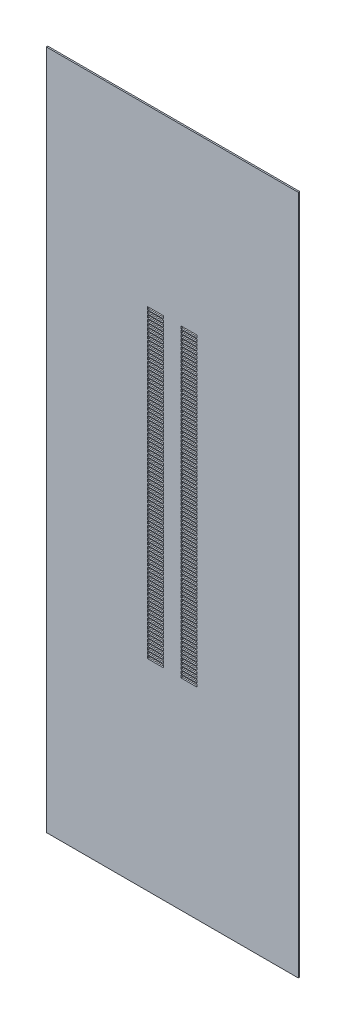
SolidWorks part; units mm, degrees
ref_plane "Front Plane" through (0, 0, 0) normal (0, 0, 1) x (1, 0, 0)
ref_plane "Top Plane" through (0, 0, 0) normal (0, 1, 0) x (1, 0, 0)
ref_plane "Right Plane" through (0, 0, 0) normal (1, 0, 0) x (0, 0, -1)
sketch "Sketch1" plane through (0, 0, 0) normal (0, 0, 1) x (1, 0, 0)
  line L1340 (-1.19, -0.37) -> (-1.19, 0)
  line L1341 (-1.19, 0) -> (-3.41, 0)
  line L1342 (-3.41, 0) -> (-3.41, -0.37)
  line L1343 (-3.41, -0.37) -> (-1.19, -0.37)
  line L2016 (-1.19, 0) -> (1.19, 0) construction
  line L2017 (0, 0) -> (0, 7.5425) construction
  line L2018 (1.19, -0.37) -> (1.19, 0)
  line L2019 (3.41, -0.37) -> (1.19, -0.37)
  line L2020 (3.41, 0) -> (3.41, -0.37)
  line L2021 (1.19, 0) -> (3.41, 0)
  line L2022 (1.19, -0.5) -> (3.41, -0.5)
  line L2023 (3.41, -0.5) -> (3.41, -0.87)
  line L2024 (3.41, -0.87) -> (1.19, -0.87)
  line L2025 (1.19, -0.87) -> (1.19, -0.5)
  line L2026 (-1.19, -0.5) -> (-3.41, -0.5)
  line L2027 (-3.41, -0.5) -> (-3.41, -0.87)
  line L2028 (-3.41, -0.87) -> (-1.19, -0.87)
  line L2029 (-1.19, -0.87) -> (-1.19, -0.5)
  line L2030 (1.19, -1) -> (3.41, -1)
  line L2031 (3.41, -1) -> (3.41, -1.37)
  line L2032 (3.41, -1.37) -> (1.19, -1.37)
  line L2033 (1.19, -1.37) -> (1.19, -1)
  line L2034 (-1.19, -1) -> (-3.41, -1)
  line L2035 (-3.41, -1) -> (-3.41, -1.37)
  line L2036 (-3.41, -1.37) -> (-1.19, -1.37)
  line L2037 (-1.19, -1.37) -> (-1.19, -1)
  line L2038 (1.19, -1.5) -> (3.41, -1.5)
  line L2039 (3.41, -1.5) -> (3.41, -1.87)
  line L2040 (3.41, -1.87) -> (1.19, -1.87)
  line L2041 (1.19, -1.87) -> (1.19, -1.5)
  line L2042 (-1.19, -1.5) -> (-3.41, -1.5)
  line L2043 (-3.41, -1.5) -> (-3.41, -1.87)
  line L2044 (-3.41, -1.87) -> (-1.19, -1.87)
  line L2045 (-1.19, -1.87) -> (-1.19, -1.5)
  line L2046 (1.19, -2) -> (3.41, -2)
  line L2047 (3.41, -2) -> (3.41, -2.37)
  line L2048 (3.41, -2.37) -> (1.19, -2.37)
  line L2049 (1.19, -2.37) -> (1.19, -2)
  line L2050 (-1.19, -2) -> (-3.41, -2)
  line L2051 (-3.41, -2) -> (-3.41, -2.37)
  line L2052 (-3.41, -2.37) -> (-1.19, -2.37)
  line L2053 (-1.19, -2.37) -> (-1.19, -2)
  line L2054 (1.19, -2.5) -> (3.41, -2.5)
  line L2055 (3.41, -2.5) -> (3.41, -2.87)
  line L2056 (3.41, -2.87) -> (1.19, -2.87)
  line L2057 (1.19, -2.87) -> (1.19, -2.5)
  line L2058 (-1.19, -2.5) -> (-3.41, -2.5)
  line L2059 (-3.41, -2.5) -> (-3.41, -2.87)
  line L2060 (-3.41, -2.87) -> (-1.19, -2.87)
  line L2061 (-1.19, -2.87) -> (-1.19, -2.5)
  line L2062 (1.19, -3) -> (3.41, -3)
  line L2063 (3.41, -3) -> (3.41, -3.37)
  line L2064 (3.41, -3.37) -> (1.19, -3.37)
  line L2065 (1.19, -3.37) -> (1.19, -3)
  line L2066 (-1.19, -3) -> (-3.41, -3)
  line L2067 (-3.41, -3) -> (-3.41, -3.37)
  line L2068 (-3.41, -3.37) -> (-1.19, -3.37)
  line L2069 (-1.19, -3.37) -> (-1.19, -3)
  line L2070 (1.19, -3.5) -> (3.41, -3.5)
  line L2071 (3.41, -3.5) -> (3.41, -3.87)
  line L2072 (3.41, -3.87) -> (1.19, -3.87)
  line L2073 (1.19, -3.87) -> (1.19, -3.5)
  line L2074 (-1.19, -3.5) -> (-3.41, -3.5)
  line L2075 (-3.41, -3.5) -> (-3.41, -3.87)
  line L2076 (-3.41, -3.87) -> (-1.19, -3.87)
  line L2077 (-1.19, -3.87) -> (-1.19, -3.5)
  line L2078 (1.19, -4) -> (3.41, -4)
  line L2079 (3.41, -4) -> (3.41, -4.37)
  line L2080 (3.41, -4.37) -> (1.19, -4.37)
  line L2081 (1.19, -4.37) -> (1.19, -4)
  line L2082 (-1.19, -4) -> (-3.41, -4)
  line L2083 (-3.41, -4) -> (-3.41, -4.37)
  line L2084 (-3.41, -4.37) -> (-1.19, -4.37)
  line L2085 (-1.19, -4.37) -> (-1.19, -4)
  line L2086 (1.19, -4.5) -> (3.41, -4.5)
  line L2087 (3.41, -4.5) -> (3.41, -4.87)
  line L2088 (3.41, -4.87) -> (1.19, -4.87)
  line L2089 (1.19, -4.87) -> (1.19, -4.5)
  line L2090 (-1.19, -4.5) -> (-3.41, -4.5)
  line L2091 (-3.41, -4.5) -> (-3.41, -4.87)
  line L2092 (-3.41, -4.87) -> (-1.19, -4.87)
  line L2093 (-1.19, -4.87) -> (-1.19, -4.5)
  line L2094 (1.19, -5) -> (3.41, -5)
  line L2095 (3.41, -5) -> (3.41, -5.37)
  line L2096 (3.41, -5.37) -> (1.19, -5.37)
  line L2097 (1.19, -5.37) -> (1.19, -5)
  line L2098 (-1.19, -5) -> (-3.41, -5)
  line L2099 (-3.41, -5) -> (-3.41, -5.37)
  line L2100 (-3.41, -5.37) -> (-1.19, -5.37)
  line L2101 (-1.19, -5.37) -> (-1.19, -5)
  line L2102 (1.19, -5.5) -> (3.41, -5.5)
  line L2103 (3.41, -5.5) -> (3.41, -5.87)
  line L2104 (3.41, -5.87) -> (1.19, -5.87)
  line L2105 (1.19, -5.87) -> (1.19, -5.5)
  line L2106 (-1.19, -5.5) -> (-3.41, -5.5)
  line L2107 (-3.41, -5.5) -> (-3.41, -5.87)
  line L2108 (-3.41, -5.87) -> (-1.19, -5.87)
  line L2109 (-1.19, -5.87) -> (-1.19, -5.5)
  line L2110 (1.19, -6) -> (3.41, -6)
  line L2111 (3.41, -6) -> (3.41, -6.37)
  line L2112 (3.41, -6.37) -> (1.19, -6.37)
  line L2113 (1.19, -6.37) -> (1.19, -6)
  line L2114 (-1.19, -6) -> (-3.41, -6)
  line L2115 (-3.41, -6) -> (-3.41, -6.37)
  line L2116 (-3.41, -6.37) -> (-1.19, -6.37)
  line L2117 (-1.19, -6.37) -> (-1.19, -6)
  line L2118 (1.19, -6.5) -> (3.41, -6.5)
  line L2119 (3.41, -6.5) -> (3.41, -6.87)
  line L2120 (3.41, -6.87) -> (1.19, -6.87)
  line L2121 (1.19, -6.87) -> (1.19, -6.5)
  line L2122 (-1.19, -6.5) -> (-3.41, -6.5)
  line L2123 (-3.41, -6.5) -> (-3.41, -6.87)
  line L2124 (-3.41, -6.87) -> (-1.19, -6.87)
  line L2125 (-1.19, -6.87) -> (-1.19, -6.5)
  line L2126 (1.19, -7) -> (3.41, -7)
  line L2127 (3.41, -7) -> (3.41, -7.37)
  line L2128 (3.41, -7.37) -> (1.19, -7.37)
  line L2129 (1.19, -7.37) -> (1.19, -7)
  line L2130 (-1.19, -7) -> (-3.41, -7)
  line L2131 (-3.41, -7) -> (-3.41, -7.37)
  line L2132 (-3.41, -7.37) -> (-1.19, -7.37)
  line L2133 (-1.19, -7.37) -> (-1.19, -7)
  line L2134 (1.19, -7.5) -> (3.41, -7.5)
  line L2135 (3.41, -7.5) -> (3.41, -7.87)
  line L2136 (3.41, -7.87) -> (1.19, -7.87)
  line L2137 (1.19, -7.87) -> (1.19, -7.5)
  line L2138 (-1.19, -7.5) -> (-3.41, -7.5)
  line L2139 (-3.41, -7.5) -> (-3.41, -7.87)
  line L2140 (-3.41, -7.87) -> (-1.19, -7.87)
  line L2141 (-1.19, -7.87) -> (-1.19, -7.5)
  line L2142 (1.19, -8) -> (3.41, -8)
  line L2143 (3.41, -8) -> (3.41, -8.37)
  line L2144 (3.41, -8.37) -> (1.19, -8.37)
  line L2145 (1.19, -8.37) -> (1.19, -8)
  line L2146 (-1.19, -8) -> (-3.41, -8)
  line L2147 (-3.41, -8) -> (-3.41, -8.37)
  line L2148 (-3.41, -8.37) -> (-1.19, -8.37)
  line L2149 (-1.19, -8.37) -> (-1.19, -8)
  line L2150 (1.19, -8.5) -> (3.41, -8.5)
  line L2151 (3.41, -8.5) -> (3.41, -8.87)
  line L2152 (3.41, -8.87) -> (1.19, -8.87)
  line L2153 (1.19, -8.87) -> (1.19, -8.5)
  line L2154 (-1.19, -8.5) -> (-3.41, -8.5)
  line L2155 (-3.41, -8.5) -> (-3.41, -8.87)
  line L2156 (-3.41, -8.87) -> (-1.19, -8.87)
  line L2157 (-1.19, -8.87) -> (-1.19, -8.5)
  line L2158 (1.19, -9) -> (3.41, -9)
  line L2159 (3.41, -9) -> (3.41, -9.37)
  line L2160 (3.41, -9.37) -> (1.19, -9.37)
  line L2161 (1.19, -9.37) -> (1.19, -9)
  line L2162 (-1.19, -9) -> (-3.41, -9)
  line L2163 (-3.41, -9) -> (-3.41, -9.37)
  line L2164 (-3.41, -9.37) -> (-1.19, -9.37)
  line L2165 (-1.19, -9.37) -> (-1.19, -9)
  line L2166 (1.19, -9.5) -> (3.41, -9.5)
  line L2167 (3.41, -9.5) -> (3.41, -9.87)
  line L2168 (3.41, -9.87) -> (1.19, -9.87)
  line L2169 (1.19, -9.87) -> (1.19, -9.5)
  line L2170 (-1.19, -9.5) -> (-3.41, -9.5)
  line L2171 (-3.41, -9.5) -> (-3.41, -9.87)
  line L2172 (-3.41, -9.87) -> (-1.19, -9.87)
  line L2173 (-1.19, -9.87) -> (-1.19, -9.5)
  line L2174 (1.19, -10) -> (3.41, -10)
  line L2175 (3.41, -10) -> (3.41, -10.37)
  line L2176 (3.41, -10.37) -> (1.19, -10.37)
  line L2177 (1.19, -10.37) -> (1.19, -10)
  line L2178 (-1.19, -10) -> (-3.41, -10)
  line L2179 (-3.41, -10) -> (-3.41, -10.37)
  line L2180 (-3.41, -10.37) -> (-1.19, -10.37)
  line L2181 (-1.19, -10.37) -> (-1.19, -10)
  line L2182 (1.19, -10.5) -> (3.41, -10.5)
  line L2183 (3.41, -10.5) -> (3.41, -10.87)
  line L2184 (3.41, -10.87) -> (1.19, -10.87)
  line L2185 (1.19, -10.87) -> (1.19, -10.5)
  line L2186 (-1.19, -10.5) -> (-3.41, -10.5)
  line L2187 (-3.41, -10.5) -> (-3.41, -10.87)
  line L2188 (-3.41, -10.87) -> (-1.19, -10.87)
  line L2189 (-1.19, -10.87) -> (-1.19, -10.5)
  line L2190 (1.19, -11) -> (3.41, -11)
  line L2191 (3.41, -11) -> (3.41, -11.37)
  line L2192 (3.41, -11.37) -> (1.19, -11.37)
  line L2193 (1.19, -11.37) -> (1.19, -11)
  line L2194 (-1.19, -11) -> (-3.41, -11)
  line L2195 (-3.41, -11) -> (-3.41, -11.37)
  line L2196 (-3.41, -11.37) -> (-1.19, -11.37)
  line L2197 (-1.19, -11.37) -> (-1.19, -11)
  line L2198 (1.19, -11.5) -> (3.41, -11.5)
  line L2199 (3.41, -11.5) -> (3.41, -11.87)
  line L2200 (3.41, -11.87) -> (1.19, -11.87)
  line L2201 (1.19, -11.87) -> (1.19, -11.5)
  line L2202 (-1.19, -11.5) -> (-3.41, -11.5)
  line L2203 (-3.41, -11.5) -> (-3.41, -11.87)
  line L2204 (-3.41, -11.87) -> (-1.19, -11.87)
  line L2205 (-1.19, -11.87) -> (-1.19, -11.5)
  line L2206 (1.19, -12) -> (3.41, -12)
  line L2207 (3.41, -12) -> (3.41, -12.37)
  line L2208 (3.41, -12.37) -> (1.19, -12.37)
  line L2209 (1.19, -12.37) -> (1.19, -12)
  line L2210 (-1.19, -12) -> (-3.41, -12)
  line L2211 (-3.41, -12) -> (-3.41, -12.37)
  line L2212 (-3.41, -12.37) -> (-1.19, -12.37)
  line L2213 (-1.19, -12.37) -> (-1.19, -12)
  line L2214 (1.19, -12.5) -> (3.41, -12.5)
  line L2215 (3.41, -12.5) -> (3.41, -12.87)
  line L2216 (3.41, -12.87) -> (1.19, -12.87)
  line L2217 (1.19, -12.87) -> (1.19, -12.5)
  line L2218 (-1.19, -12.5) -> (-3.41, -12.5)
  line L2219 (-3.41, -12.5) -> (-3.41, -12.87)
  line L2220 (-3.41, -12.87) -> (-1.19, -12.87)
  line L2221 (-1.19, -12.87) -> (-1.19, -12.5)
  line L2222 (1.19, -13) -> (3.41, -13)
  line L2223 (3.41, -13) -> (3.41, -13.37)
  line L2224 (3.41, -13.37) -> (1.19, -13.37)
  line L2225 (1.19, -13.37) -> (1.19, -13)
  line L2226 (-1.19, -13) -> (-3.41, -13)
  line L2227 (-3.41, -13) -> (-3.41, -13.37)
  line L2228 (-3.41, -13.37) -> (-1.19, -13.37)
  line L2229 (-1.19, -13.37) -> (-1.19, -13)
  line L2230 (1.19, -13.5) -> (3.41, -13.5)
  line L2231 (3.41, -13.5) -> (3.41, -13.87)
  line L2232 (3.41, -13.87) -> (1.19, -13.87)
  line L2233 (1.19, -13.87) -> (1.19, -13.5)
  line L2234 (-1.19, -13.5) -> (-3.41, -13.5)
  line L2235 (-3.41, -13.5) -> (-3.41, -13.87)
  line L2236 (-3.41, -13.87) -> (-1.19, -13.87)
  line L2237 (-1.19, -13.87) -> (-1.19, -13.5)
  line L2238 (1.19, -14) -> (3.41, -14)
  line L2239 (3.41, -14) -> (3.41, -14.37)
  line L2240 (3.41, -14.37) -> (1.19, -14.37)
  line L2241 (1.19, -14.37) -> (1.19, -14)
  line L2242 (-1.19, -14) -> (-3.41, -14)
  line L2243 (-3.41, -14) -> (-3.41, -14.37)
  line L2244 (-3.41, -14.37) -> (-1.19, -14.37)
  line L2245 (-1.19, -14.37) -> (-1.19, -14)
  line L2246 (1.19, -14.5) -> (3.41, -14.5)
  line L2247 (3.41, -14.5) -> (3.41, -14.87)
  line L2248 (3.41, -14.87) -> (1.19, -14.87)
  line L2249 (1.19, -14.87) -> (1.19, -14.5)
  line L2250 (-1.19, -14.5) -> (-3.41, -14.5)
  line L2251 (-3.41, -14.5) -> (-3.41, -14.87)
  line L2252 (-3.41, -14.87) -> (-1.19, -14.87)
  line L2253 (-1.19, -14.87) -> (-1.19, -14.5)
  line L2254 (1.19, -15) -> (3.41, -15)
  line L2255 (3.41, -15) -> (3.41, -15.37)
  line L2256 (3.41, -15.37) -> (1.19, -15.37)
  line L2257 (1.19, -15.37) -> (1.19, -15)
  line L2258 (-1.19, -15) -> (-3.41, -15)
  line L2259 (-3.41, -15) -> (-3.41, -15.37)
  line L2260 (-3.41, -15.37) -> (-1.19, -15.37)
  line L2261 (-1.19, -15.37) -> (-1.19, -15)
  line L2262 (1.19, -15.5) -> (3.41, -15.5)
  line L2263 (3.41, -15.5) -> (3.41, -15.87)
  line L2264 (3.41, -15.87) -> (1.19, -15.87)
  line L2265 (1.19, -15.87) -> (1.19, -15.5)
  line L2266 (-1.19, -15.5) -> (-3.41, -15.5)
  line L2267 (-3.41, -15.5) -> (-3.41, -15.87)
  line L2268 (-3.41, -15.87) -> (-1.19, -15.87)
  line L2269 (-1.19, -15.87) -> (-1.19, -15.5)
  line L2270 (1.19, -16) -> (3.41, -16)
  line L2271 (3.41, -16) -> (3.41, -16.37)
  line L2272 (3.41, -16.37) -> (1.19, -16.37)
  line L2273 (1.19, -16.37) -> (1.19, -16)
  line L2274 (-1.19, -16) -> (-3.41, -16)
  line L2275 (-3.41, -16) -> (-3.41, -16.37)
  line L2276 (-3.41, -16.37) -> (-1.19, -16.37)
  line L2277 (-1.19, -16.37) -> (-1.19, -16)
  line L2278 (1.19, -16.5) -> (3.41, -16.5)
  line L2279 (3.41, -16.5) -> (3.41, -16.87)
  line L2280 (3.41, -16.87) -> (1.19, -16.87)
  line L2281 (1.19, -16.87) -> (1.19, -16.5)
  line L2282 (-1.19, -16.5) -> (-3.41, -16.5)
  line L2283 (-3.41, -16.5) -> (-3.41, -16.87)
  line L2284 (-3.41, -16.87) -> (-1.19, -16.87)
  line L2285 (-1.19, -16.87) -> (-1.19, -16.5)
  line L2286 (1.19, -17) -> (3.41, -17)
  line L2287 (3.41, -17) -> (3.41, -17.37)
  line L2288 (3.41, -17.37) -> (1.19, -17.37)
  line L2289 (1.19, -17.37) -> (1.19, -17)
  line L2290 (-1.19, -17) -> (-3.41, -17)
  line L2291 (-3.41, -17) -> (-3.41, -17.37)
  line L2292 (-3.41, -17.37) -> (-1.19, -17.37)
  line L2293 (-1.19, -17.37) -> (-1.19, -17)
  line L2294 (1.19, -17.5) -> (3.41, -17.5)
  line L2295 (3.41, -17.5) -> (3.41, -17.87)
  line L2296 (3.41, -17.87) -> (1.19, -17.87)
  line L2297 (1.19, -17.87) -> (1.19, -17.5)
  line L2298 (-1.19, -17.5) -> (-3.41, -17.5)
  line L2299 (-3.41, -17.5) -> (-3.41, -17.87)
  line L2300 (-3.41, -17.87) -> (-1.19, -17.87)
  line L2301 (-1.19, -17.87) -> (-1.19, -17.5)
  line L2302 (1.19, -18) -> (3.41, -18)
  line L2303 (3.41, -18) -> (3.41, -18.37)
  line L2304 (3.41, -18.37) -> (1.19, -18.37)
  line L2305 (1.19, -18.37) -> (1.19, -18)
  line L2306 (-1.19, -18) -> (-3.41, -18)
  line L2307 (-3.41, -18) -> (-3.41, -18.37)
  line L2308 (-3.41, -18.37) -> (-1.19, -18.37)
  line L2309 (-1.19, -18.37) -> (-1.19, -18)
  line L2310 (1.19, -18.5) -> (3.41, -18.5)
  line L2311 (3.41, -18.5) -> (3.41, -18.87)
  line L2312 (3.41, -18.87) -> (1.19, -18.87)
  line L2313 (1.19, -18.87) -> (1.19, -18.5)
  line L2314 (-1.19, -18.5) -> (-3.41, -18.5)
  line L2315 (-3.41, -18.5) -> (-3.41, -18.87)
  line L2316 (-3.41, -18.87) -> (-1.19, -18.87)
  line L2317 (-1.19, -18.87) -> (-1.19, -18.5)
  line L2318 (1.19, -19) -> (3.41, -19)
  line L2319 (3.41, -19) -> (3.41, -19.37)
  line L2320 (3.41, -19.37) -> (1.19, -19.37)
  line L2321 (1.19, -19.37) -> (1.19, -19)
  line L2322 (-1.19, -19) -> (-3.41, -19)
  line L2323 (-3.41, -19) -> (-3.41, -19.37)
  line L2324 (-3.41, -19.37) -> (-1.19, -19.37)
  line L2325 (-1.19, -19.37) -> (-1.19, -19)
  line L2326 (1.19, -19.5) -> (3.41, -19.5)
  line L2327 (3.41, -19.5) -> (3.41, -19.87)
  line L2328 (3.41, -19.87) -> (1.19, -19.87)
  line L2329 (1.19, -19.87) -> (1.19, -19.5)
  line L2330 (-1.19, -19.5) -> (-3.41, -19.5)
  line L2331 (-3.41, -19.5) -> (-3.41, -19.87)
  line L2332 (-3.41, -19.87) -> (-1.19, -19.87)
  line L2333 (-1.19, -19.87) -> (-1.19, -19.5)
  line L2334 (1.19, -20) -> (3.41, -20)
  line L2335 (3.41, -20) -> (3.41, -20.37)
  line L2336 (3.41, -20.37) -> (1.19, -20.37)
  line L2337 (1.19, -20.37) -> (1.19, -20)
  line L2338 (-1.19, -20) -> (-3.41, -20)
  line L2339 (-3.41, -20) -> (-3.41, -20.37)
  line L2340 (-3.41, -20.37) -> (-1.19, -20.37)
  line L2341 (-1.19, -20.37) -> (-1.19, -20)
  line L2342 (1.19, -20.5) -> (3.41, -20.5)
  line L2343 (3.41, -20.5) -> (3.41, -20.87)
  line L2344 (3.41, -20.87) -> (1.19, -20.87)
  line L2345 (1.19, -20.87) -> (1.19, -20.5)
  line L2346 (-1.19, -20.5) -> (-3.41, -20.5)
  line L2347 (-3.41, -20.5) -> (-3.41, -20.87)
  line L2348 (-3.41, -20.87) -> (-1.19, -20.87)
  line L2349 (-1.19, -20.87) -> (-1.19, -20.5)
  line L2350 (1.19, -21) -> (3.41, -21)
  line L2351 (3.41, -21) -> (3.41, -21.37)
  line L2352 (3.41, -21.37) -> (1.19, -21.37)
  line L2353 (1.19, -21.37) -> (1.19, -21)
  line L2354 (-1.19, -21) -> (-3.41, -21)
  line L2355 (-3.41, -21) -> (-3.41, -21.37)
  line L2356 (-3.41, -21.37) -> (-1.19, -21.37)
  line L2357 (-1.19, -21.37) -> (-1.19, -21)
  line L2358 (1.19, -21.5) -> (3.41, -21.5)
  line L2359 (3.41, -21.5) -> (3.41, -21.87)
  line L2360 (3.41, -21.87) -> (1.19, -21.87)
  line L2361 (1.19, -21.87) -> (1.19, -21.5)
  line L2362 (-1.19, -21.5) -> (-3.41, -21.5)
  line L2363 (-3.41, -21.5) -> (-3.41, -21.87)
  line L2364 (-3.41, -21.87) -> (-1.19, -21.87)
  line L2365 (-1.19, -21.87) -> (-1.19, -21.5)
  line L2366 (1.19, -22) -> (3.41, -22)
  line L2367 (3.41, -22) -> (3.41, -22.37)
  line L2368 (3.41, -22.37) -> (1.19, -22.37)
  line L2369 (1.19, -22.37) -> (1.19, -22)
  line L2370 (-1.19, -22) -> (-3.41, -22)
  line L2371 (-3.41, -22) -> (-3.41, -22.37)
  line L2372 (-3.41, -22.37) -> (-1.19, -22.37)
  line L2373 (-1.19, -22.37) -> (-1.19, -22)
  line L2374 (1.19, -22.5) -> (3.41, -22.5)
  line L2375 (3.41, -22.5) -> (3.41, -22.87)
  line L2376 (3.41, -22.87) -> (1.19, -22.87)
  line L2377 (1.19, -22.87) -> (1.19, -22.5)
  line L2378 (-1.19, -22.5) -> (-3.41, -22.5)
  line L2379 (-3.41, -22.5) -> (-3.41, -22.87)
  line L2380 (-3.41, -22.87) -> (-1.19, -22.87)
  line L2381 (-1.19, -22.87) -> (-1.19, -22.5)
  line L2382 (1.19, -23) -> (3.41, -23)
  line L2383 (3.41, -23) -> (3.41, -23.37)
  line L2384 (3.41, -23.37) -> (1.19, -23.37)
  line L2385 (1.19, -23.37) -> (1.19, -23)
  line L2386 (-1.19, -23) -> (-3.41, -23)
  line L2387 (-3.41, -23) -> (-3.41, -23.37)
  line L2388 (-3.41, -23.37) -> (-1.19, -23.37)
  line L2389 (-1.19, -23.37) -> (-1.19, -23)
  line L2390 (1.19, -23.5) -> (3.41, -23.5)
  line L2391 (3.41, -23.5) -> (3.41, -23.87)
  line L2392 (3.41, -23.87) -> (1.19, -23.87)
  line L2393 (1.19, -23.87) -> (1.19, -23.5)
  line L2394 (-1.19, -23.5) -> (-3.41, -23.5)
  line L2395 (-3.41, -23.5) -> (-3.41, -23.87)
  line L2396 (-3.41, -23.87) -> (-1.19, -23.87)
  line L2397 (-1.19, -23.87) -> (-1.19, -23.5)
  line L2398 (1.19, -24) -> (3.41, -24)
  line L2399 (3.41, -24) -> (3.41, -24.37)
  line L2400 (3.41, -24.37) -> (1.19, -24.37)
  line L2401 (1.19, -24.37) -> (1.19, -24)
  line L2402 (-1.19, -24) -> (-3.41, -24)
  line L2403 (-3.41, -24) -> (-3.41, -24.37)
  line L2404 (-3.41, -24.37) -> (-1.19, -24.37)
  line L2405 (-1.19, -24.37) -> (-1.19, -24)
  line L2406 (1.19, -24.5) -> (3.41, -24.5)
  line L2407 (3.41, -24.5) -> (3.41, -24.87)
  line L2408 (3.41, -24.87) -> (1.19, -24.87)
  line L2409 (1.19, -24.87) -> (1.19, -24.5)
  line L2410 (-1.19, -24.5) -> (-3.41, -24.5)
  line L2411 (-3.41, -24.5) -> (-3.41, -24.87)
  line L2412 (-3.41, -24.87) -> (-1.19, -24.87)
  line L2413 (-1.19, -24.87) -> (-1.19, -24.5)
  line L2414 (1.19, -25) -> (3.41, -25)
  line L2415 (3.41, -25) -> (3.41, -25.37)
  line L2416 (3.41, -25.37) -> (1.19, -25.37)
  line L2417 (1.19, -25.37) -> (1.19, -25)
  line L2418 (-1.19, -25) -> (-3.41, -25)
  line L2419 (-3.41, -25) -> (-3.41, -25.37)
  line L2420 (-3.41, -25.37) -> (-1.19, -25.37)
  line L2421 (-1.19, -25.37) -> (-1.19, -25)
  line L2422 (1.19, -25.5) -> (3.41, -25.5)
  line L2423 (3.41, -25.5) -> (3.41, -25.87)
  line L2424 (3.41, -25.87) -> (1.19, -25.87)
  line L2425 (1.19, -25.87) -> (1.19, -25.5)
  line L2426 (-1.19, -25.5) -> (-3.41, -25.5)
  line L2427 (-3.41, -25.5) -> (-3.41, -25.87)
  line L2428 (-3.41, -25.87) -> (-1.19, -25.87)
  line L2429 (-1.19, -25.87) -> (-1.19, -25.5)
  line L2430 (1.19, -26) -> (3.41, -26)
  line L2431 (3.41, -26) -> (3.41, -26.37)
  line L2432 (3.41, -26.37) -> (1.19, -26.37)
  line L2433 (1.19, -26.37) -> (1.19, -26)
  line L2434 (-1.19, -26) -> (-3.41, -26)
  line L2435 (-3.41, -26) -> (-3.41, -26.37)
  line L2436 (-3.41, -26.37) -> (-1.19, -26.37)
  line L2437 (-1.19, -26.37) -> (-1.19, -26)
  line L2438 (1.19, -26.5) -> (3.41, -26.5)
  line L2439 (3.41, -26.5) -> (3.41, -26.87)
  line L2440 (3.41, -26.87) -> (1.19, -26.87)
  line L2441 (1.19, -26.87) -> (1.19, -26.5)
  line L2442 (-1.19, -26.5) -> (-3.41, -26.5)
  line L2443 (-3.41, -26.5) -> (-3.41, -26.87)
  line L2444 (-3.41, -26.87) -> (-1.19, -26.87)
  line L2445 (-1.19, -26.87) -> (-1.19, -26.5)
  line L2446 (1.19, -27) -> (3.41, -27)
  line L2447 (3.41, -27) -> (3.41, -27.37)
  line L2448 (3.41, -27.37) -> (1.19, -27.37)
  line L2449 (1.19, -27.37) -> (1.19, -27)
  line L2450 (-1.19, -27) -> (-3.41, -27)
  line L2451 (-3.41, -27) -> (-3.41, -27.37)
  line L2452 (-3.41, -27.37) -> (-1.19, -27.37)
  line L2453 (-1.19, -27.37) -> (-1.19, -27)
  line L2454 (1.19, -27.5) -> (3.41, -27.5)
  line L2455 (3.41, -27.5) -> (3.41, -27.87)
  line L2456 (3.41, -27.87) -> (1.19, -27.87)
  line L2457 (1.19, -27.87) -> (1.19, -27.5)
  line L2458 (-1.19, -27.5) -> (-3.41, -27.5)
  line L2459 (-3.41, -27.5) -> (-3.41, -27.87)
  line L2460 (-3.41, -27.87) -> (-1.19, -27.87)
  line L2461 (-1.19, -27.87) -> (-1.19, -27.5)
  line L2462 (1.19, -28) -> (3.41, -28)
  line L2463 (3.41, -28) -> (3.41, -28.37)
  line L2464 (3.41, -28.37) -> (1.19, -28.37)
  line L2465 (1.19, -28.37) -> (1.19, -28)
  line L2466 (-1.19, -28) -> (-3.41, -28)
  line L2467 (-3.41, -28) -> (-3.41, -28.37)
  line L2468 (-3.41, -28.37) -> (-1.19, -28.37)
  line L2469 (-1.19, -28.37) -> (-1.19, -28)
  line L2470 (1.19, -28.5) -> (3.41, -28.5)
  line L2471 (3.41, -28.5) -> (3.41, -28.87)
  line L2472 (3.41, -28.87) -> (1.19, -28.87)
  line L2473 (1.19, -28.87) -> (1.19, -28.5)
  line L2474 (-1.19, -28.5) -> (-3.41, -28.5)
  line L2475 (-3.41, -28.5) -> (-3.41, -28.87)
  line L2476 (-3.41, -28.87) -> (-1.19, -28.87)
  line L2477 (-1.19, -28.87) -> (-1.19, -28.5)
  line L2478 (1.19, -29) -> (3.41, -29)
  line L2479 (3.41, -29) -> (3.41, -29.37)
  line L2480 (3.41, -29.37) -> (1.19, -29.37)
  line L2481 (1.19, -29.37) -> (1.19, -29)
  line L2482 (-1.19, -29) -> (-3.41, -29)
  line L2483 (-3.41, -29) -> (-3.41, -29.37)
  line L2484 (-3.41, -29.37) -> (-1.19, -29.37)
  line L2485 (-1.19, -29.37) -> (-1.19, -29)
  line L2486 (1.19, -29.5) -> (3.41, -29.5)
  line L2487 (3.41, -29.5) -> (3.41, -29.87)
  line L2488 (3.41, -29.87) -> (1.19, -29.87)
  line L2489 (1.19, -29.87) -> (1.19, -29.5)
  line L2490 (-1.19, -29.5) -> (-3.41, -29.5)
  line L2491 (-3.41, -29.5) -> (-3.41, -29.87)
  line L2492 (-3.41, -29.87) -> (-1.19, -29.87)
  line L2493 (-1.19, -29.87) -> (-1.19, -29.5)
  line L2494 (1.19, -30) -> (3.41, -30)
  line L2495 (3.41, -30) -> (3.41, -30.37)
  line L2496 (3.41, -30.37) -> (1.19, -30.37)
  line L2497 (1.19, -30.37) -> (1.19, -30)
  line L2498 (-1.19, -30) -> (-3.41, -30)
  line L2499 (-3.41, -30) -> (-3.41, -30.37)
  line L2500 (-3.41, -30.37) -> (-1.19, -30.37)
  line L2501 (-1.19, -30.37) -> (-1.19, -30)
  line L2502 (1.19, -30.5) -> (3.41, -30.5)
  line L2503 (3.41, -30.5) -> (3.41, -30.87)
  line L2504 (3.41, -30.87) -> (1.19, -30.87)
  line L2505 (1.19, -30.87) -> (1.19, -30.5)
  line L2506 (-1.19, -30.5) -> (-3.41, -30.5)
  line L2507 (-3.41, -30.5) -> (-3.41, -30.87)
  line L2508 (-3.41, -30.87) -> (-1.19, -30.87)
  line L2509 (-1.19, -30.87) -> (-1.19, -30.5)
  line L2510 (1.19, -31) -> (3.41, -31)
  line L2511 (3.41, -31) -> (3.41, -31.37)
  line L2512 (3.41, -31.37) -> (1.19, -31.37)
  line L2513 (1.19, -31.37) -> (1.19, -31)
  line L2514 (-1.19, -31) -> (-3.41, -31)
  line L2515 (-3.41, -31) -> (-3.41, -31.37)
  line L2516 (-3.41, -31.37) -> (-1.19, -31.37)
  line L2517 (-1.19, -31.37) -> (-1.19, -31)
  line L2518 (1.19, -31.5) -> (3.41, -31.5)
  line L2519 (3.41, -31.5) -> (3.41, -31.87)
  line L2520 (3.41, -31.87) -> (1.19, -31.87)
  line L2521 (1.19, -31.87) -> (1.19, -31.5)
  line L2522 (-1.19, -31.5) -> (-3.41, -31.5)
  line L2523 (-3.41, -31.5) -> (-3.41, -31.87)
  line L2524 (-3.41, -31.87) -> (-1.19, -31.87)
  line L2525 (-1.19, -31.87) -> (-1.19, -31.5)
  line L2526 (1.19, -32) -> (3.41, -32)
  line L2527 (3.41, -32) -> (3.41, -32.37)
  line L2528 (3.41, -32.37) -> (1.19, -32.37)
  line L2529 (1.19, -32.37) -> (1.19, -32)
  line L2530 (-1.19, -32) -> (-3.41, -32)
  line L2531 (-3.41, -32) -> (-3.41, -32.37)
  line L2532 (-3.41, -32.37) -> (-1.19, -32.37)
  line L2533 (-1.19, -32.37) -> (-1.19, -32)
  line L2534 (1.19, -32.5) -> (3.41, -32.5)
  line L2535 (3.41, -32.5) -> (3.41, -32.87)
  line L2536 (3.41, -32.87) -> (1.19, -32.87)
  line L2537 (1.19, -32.87) -> (1.19, -32.5)
  line L2538 (-1.19, -32.5) -> (-3.41, -32.5)
  line L2539 (-3.41, -32.5) -> (-3.41, -32.87)
  line L2540 (-3.41, -32.87) -> (-1.19, -32.87)
  line L2541 (-1.19, -32.87) -> (-1.19, -32.5)
  line L2542 (1.19, -33) -> (3.41, -33)
  line L2543 (3.41, -33) -> (3.41, -33.37)
  line L2544 (3.41, -33.37) -> (1.19, -33.37)
  line L2545 (1.19, -33.37) -> (1.19, -33)
  line L2546 (-1.19, -33) -> (-3.41, -33)
  line L2547 (-3.41, -33) -> (-3.41, -33.37)
  line L2548 (-3.41, -33.37) -> (-1.19, -33.37)
  line L2549 (-1.19, -33.37) -> (-1.19, -33)
  line L2550 (1.19, -33.5) -> (3.41, -33.5)
  line L2551 (3.41, -33.5) -> (3.41, -33.87)
  line L2552 (3.41, -33.87) -> (1.19, -33.87)
  line L2553 (1.19, -33.87) -> (1.19, -33.5)
  line L2554 (-1.19, -33.5) -> (-3.41, -33.5)
  line L2555 (-3.41, -33.5) -> (-3.41, -33.87)
  line L2556 (-3.41, -33.87) -> (-1.19, -33.87)
  line L2557 (-1.19, -33.87) -> (-1.19, -33.5)
  line L2558 (1.19, -34) -> (3.41, -34)
  line L2559 (3.41, -34) -> (3.41, -34.37)
  line L2560 (3.41, -34.37) -> (1.19, -34.37)
  line L2561 (1.19, -34.37) -> (1.19, -34)
  line L2562 (-1.19, -34) -> (-3.41, -34)
  line L2563 (-3.41, -34) -> (-3.41, -34.37)
  line L2564 (-3.41, -34.37) -> (-1.19, -34.37)
  line L2565 (-1.19, -34.37) -> (-1.19, -34)
  line L2566 (1.19, -34.5) -> (3.41, -34.5)
  line L2567 (3.41, -34.5) -> (3.41, -34.87)
  line L2568 (3.41, -34.87) -> (1.19, -34.87)
  line L2569 (1.19, -34.87) -> (1.19, -34.5)
  line L2570 (-1.19, -34.5) -> (-3.41, -34.5)
  line L2571 (-3.41, -34.5) -> (-3.41, -34.87)
  line L2572 (-3.41, -34.87) -> (-1.19, -34.87)
  line L2573 (-1.19, -34.87) -> (-1.19, -34.5)
  line L2574 (1.19, -35) -> (3.41, -35)
  line L2575 (3.41, -35) -> (3.41, -35.37)
  line L2576 (3.41, -35.37) -> (1.19, -35.37)
  line L2577 (1.19, -35.37) -> (1.19, -35)
  line L2578 (-1.19, -35) -> (-3.41, -35)
  line L2579 (-3.41, -35) -> (-3.41, -35.37)
  line L2580 (-3.41, -35.37) -> (-1.19, -35.37)
  line L2581 (-1.19, -35.37) -> (-1.19, -35)
  line L2582 (1.19, -35.5) -> (3.41, -35.5)
  line L2583 (3.41, -35.5) -> (3.41, -35.87)
  line L2584 (3.41, -35.87) -> (1.19, -35.87)
  line L2585 (1.19, -35.87) -> (1.19, -35.5)
  line L2586 (-1.19, -35.5) -> (-3.41, -35.5)
  line L2587 (-3.41, -35.5) -> (-3.41, -35.87)
  line L2588 (-3.41, -35.87) -> (-1.19, -35.87)
  line L2589 (-1.19, -35.87) -> (-1.19, -35.5)
  line L2590 (1.19, -36) -> (3.41, -36)
  line L2591 (3.41, -36) -> (3.41, -36.37)
  line L2592 (3.41, -36.37) -> (1.19, -36.37)
  line L2593 (1.19, -36.37) -> (1.19, -36)
  line L2594 (-1.19, -36) -> (-3.41, -36)
  line L2595 (-3.41, -36) -> (-3.41, -36.37)
  line L2596 (-3.41, -36.37) -> (-1.19, -36.37)
  line L2597 (-1.19, -36.37) -> (-1.19, -36)
  line L2598 (1.19, -36.5) -> (3.41, -36.5)
  line L2599 (3.41, -36.5) -> (3.41, -36.87)
  line L2600 (3.41, -36.87) -> (1.19, -36.87)
  line L2601 (1.19, -36.87) -> (1.19, -36.5)
  line L2602 (-1.19, -36.5) -> (-3.41, -36.5)
  line L2603 (-3.41, -36.5) -> (-3.41, -36.87)
  line L2604 (-3.41, -36.87) -> (-1.19, -36.87)
  line L2605 (-1.19, -36.87) -> (-1.19, -36.5)
  line L2606 (1.19, -37) -> (3.41, -37)
  line L2607 (3.41, -37) -> (3.41, -37.37)
  line L2608 (3.41, -37.37) -> (1.19, -37.37)
  line L2609 (1.19, -37.37) -> (1.19, -37)
  line L2610 (-1.19, -37) -> (-3.41, -37)
  line L2611 (-3.41, -37) -> (-3.41, -37.37)
  line L2612 (-3.41, -37.37) -> (-1.19, -37.37)
  line L2613 (-1.19, -37.37) -> (-1.19, -37)
  line L2614 (1.19, -37.5) -> (3.41, -37.5)
  line L2615 (3.41, -37.5) -> (3.41, -37.87)
  line L2616 (3.41, -37.87) -> (1.19, -37.87)
  line L2617 (1.19, -37.87) -> (1.19, -37.5)
  line L2618 (-1.19, -37.5) -> (-3.41, -37.5)
  line L2619 (-3.41, -37.5) -> (-3.41, -37.87)
  line L2620 (-3.41, -37.87) -> (-1.19, -37.87)
  line L2621 (-1.19, -37.87) -> (-1.19, -37.5)
  line L2622 (1.19, -38) -> (3.41, -38)
  line L2623 (3.41, -38) -> (3.41, -38.37)
  line L2624 (3.41, -38.37) -> (1.19, -38.37)
  line L2625 (1.19, -38.37) -> (1.19, -38)
  line L2626 (-1.19, -38) -> (-3.41, -38)
  line L2627 (-3.41, -38) -> (-3.41, -38.37)
  line L2628 (-3.41, -38.37) -> (-1.19, -38.37)
  line L2629 (-1.19, -38.37) -> (-1.19, -38)
  line L2630 (1.19, -38.5) -> (3.41, -38.5)
  line L2631 (3.41, -38.5) -> (3.41, -38.87)
  line L2632 (3.41, -38.87) -> (1.19, -38.87)
  line L2633 (1.19, -38.87) -> (1.19, -38.5)
  line L2634 (-1.19, -38.5) -> (-3.41, -38.5)
  line L2635 (-3.41, -38.5) -> (-3.41, -38.87)
  line L2636 (-3.41, -38.87) -> (-1.19, -38.87)
  line L2637 (-1.19, -38.87) -> (-1.19, -38.5)
  line L2638 (1.19, -39) -> (3.41, -39)
  line L2639 (3.41, -39) -> (3.41, -39.37)
  line L2640 (3.41, -39.37) -> (1.19, -39.37)
  line L2641 (1.19, -39.37) -> (1.19, -39)
  line L2642 (-1.19, -39) -> (-3.41, -39)
  line L2643 (-3.41, -39) -> (-3.41, -39.37)
  line L2644 (-3.41, -39.37) -> (-1.19, -39.37)
  line L2645 (-1.19, -39.37) -> (-1.19, -39)
  line L2646 (1.19, -39.5) -> (3.41, -39.5)
  line L2647 (3.41, -39.5) -> (3.41, -39.87)
  line L2648 (3.41, -39.87) -> (1.19, -39.87)
  line L2649 (1.19, -39.87) -> (1.19, -39.5)
  line L2650 (-1.19, -39.5) -> (-3.41, -39.5)
  line L2651 (-3.41, -39.5) -> (-3.41, -39.87)
  line L2652 (-3.41, -39.87) -> (-1.19, -39.87)
  line L2653 (-1.19, -39.87) -> (-1.19, -39.5)
  line L2654 (1.19, -40) -> (3.41, -40)
  line L2655 (3.41, -40) -> (3.41, -40.37)
  line L2656 (3.41, -40.37) -> (1.19, -40.37)
  line L2657 (1.19, -40.37) -> (1.19, -40)
  line L2658 (-1.19, -40) -> (-3.41, -40)
  line L2659 (-3.41, -40) -> (-3.41, -40.37)
  line L2660 (-3.41, -40.37) -> (-1.19, -40.37)
  line L2661 (-1.19, -40.37) -> (-1.19, -40)
  line L2662 (1.19, -40.5) -> (3.41, -40.5)
  line L2663 (3.41, -40.5) -> (3.41, -40.87)
  line L2664 (3.41, -40.87) -> (1.19, -40.87)
  line L2665 (1.19, -40.87) -> (1.19, -40.5)
  line L2666 (-1.19, -40.5) -> (-3.41, -40.5)
  line L2667 (-3.41, -40.5) -> (-3.41, -40.87)
  line L2668 (-3.41, -40.87) -> (-1.19, -40.87)
  line L2669 (-1.19, -40.87) -> (-1.19, -40.5)
  line L2670 (1.19, -41) -> (3.41, -41)
  line L2671 (3.41, -41) -> (3.41, -41.37)
  line L2672 (3.41, -41.37) -> (1.19, -41.37)
  line L2673 (1.19, -41.37) -> (1.19, -41)
  line L2674 (-1.19, -41) -> (-3.41, -41)
  line L2675 (-3.41, -41) -> (-3.41, -41.37)
  line L2676 (-3.41, -41.37) -> (-1.19, -41.37)
  line L2677 (-1.19, -41.37) -> (-1.19, -41)
  line L2678 (1.19, -41.5) -> (3.41, -41.5)
  line L2679 (3.41, -41.5) -> (3.41, -41.87)
  line L2680 (3.41, -41.87) -> (1.19, -41.87)
  line L2681 (1.19, -41.87) -> (1.19, -41.5)
  line L2682 (-1.19, -41.5) -> (-3.41, -41.5)
  line L2683 (-3.41, -41.5) -> (-3.41, -41.87)
  line L2684 (-3.41, -41.87) -> (-1.19, -41.87)
  line L2685 (-1.19, -41.87) -> (-1.19, -41.5)
  line L2686 (-17.3052, 23.9361) -> (17.3052, 23.9361)
  line L2687 (17.3052, 23.9361) -> (17.3052, -69.5061)
  line L2688 (17.3052, -69.5061) -> (-17.3052, -69.5061)
  line L2689 (-17.3052, -69.5061) -> (-17.3052, 23.9361)
  point P676 (0, 0)
  point P677 (0, 0)
  point P678 (17.3052, -69.5061)
  point P679 (-2.3, 0)
  point P680 (2.3, 0)
  dimension "D2" = 84
  dimension "D3" = 0.37
  dimension "D4" = 2.22
  dimension "D5" = 0.5
  dimension "D1" = 4.6
extrude "Boss.-Extru.1" add sketch "Sketch1" along normal blind 0.2
